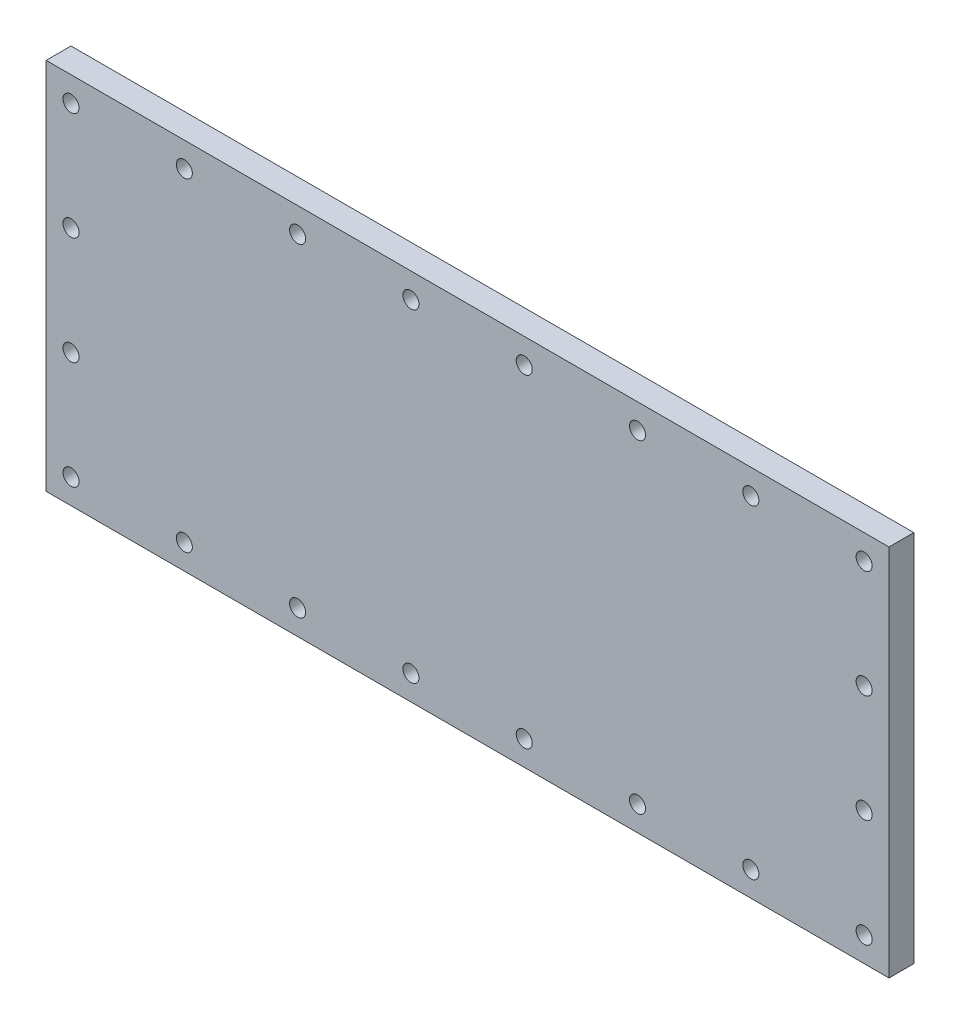
SolidWorks part; units mm, degrees
material "Acrylic (Medium-high impact)"
ref_plane "Front Plane" through (0, 0, 0) normal (0, 0, 1) x (1, 0, 0)
ref_plane "Top Plane" through (0, 0, 0) normal (0, 1, 0) x (1, 0, 0)
ref_plane "Right Plane" through (0, 0, 0) normal (1, 0, 0) x (0, 0, -1)
sketch "Sketch1" plane through (0, 0, 0) normal (0, 0, 1) x (1, 0, 0)
  line L1 (-53.85, -23.85) -> (53.85, -23.85)
  line L2 (-53.85, -23.85) -> (-53.85, 23.85)
  line L3 (-53.85, 23.85) -> (53.85, 23.85)
  line L4 (53.85, -23.85) -> (53.85, 23.85)
  line L5 (-53.85, -23.85) -> (53.85, 23.85) construction
  line L6 (-53.85, 23.85) -> (53.85, -23.85) construction
  line L7 (-50.675, 20.675) -> (50.675, 20.675) construction
  line L8 (-50.675, 20.675) -> (-50.675, -20.675) construction
  line L9 (-50.675, -20.675) -> (50.675, -20.675) construction
  line L10 (50.675, 20.675) -> (50.675, -20.675) construction
  line L11 (-47.5, 17.5) -> (47.5, 17.5)
  line L12 (-47.5, 17.5) -> (-47.5, -17.5)
  line L13 (-47.5, -17.5) -> (47.5, -17.5)
  line L14 (47.5, 17.5) -> (47.5, -17.5)
  circle A0 centre (-50.675, 20.675) radius 1.025
  circle A1 centre (50.675, 20.675) radius 1.025
  circle A2 centre (-50.675, -20.675) radius 1.025
  circle A3 centre (50.675, -20.675) radius 1.025
  circle A4 centre (-7.2393, 20.675) radius 1.025
  circle A5 centre (-7.2393, -20.675) radius 1.025
  circle A8 centre (-36.1964, 20.675) radius 1.025
  circle A9 centre (-21.7179, 20.675) radius 1.025
  circle A10 centre (7.2393, 20.675) radius 1.025
  circle A11 centre (21.7179, 20.675) radius 1.025
  circle A12 centre (-50.675, 6.8917) radius 1.025
  circle A13 centre (-50.675, -6.8917) radius 1.025
  circle A14 centre (50.675, 6.8917) radius 1.025
  circle A15 centre (50.675, -6.8917) radius 1.025
  circle A16 centre (7.2393, -20.675) radius 1.025
  circle A17 centre (21.7179, -20.675) radius 1.025
  circle A18 centre (-21.7179, -20.675) radius 1.025
  circle A19 centre (-36.1964, -20.675) radius 1.025
  circle A20 centre (36.1964, 20.675) radius 1.025
  circle A21 centre (36.1964, -20.675) radius 1.025
  point P0 (0, 0)
  dimension "D7" = 2.05
  dimension "D1" = 107.7
  dimension "D2" = 47.7
  dimension "D3" = 3.175
  dimension "D4" = 3.175
  dimension "D5" = 3.175
  dimension "D6" = 3.175
  dimension "D8" = 41.35
  dimension "D9" = 13.7833
  dimension "D10" = 13.7833
  dimension "D11" = 101.35
  dimension "D12" = 14.4786
  dimension "D13" = 14.4786
  dimension "D14" = 14.4786
  dimension "D15" = 14.4786
  dimension "D16" = 6.35
  dimension "D17" = 6.35
  dimension "D18" = 6.35
  dimension "D19" = 6.35
  dimension "D20" = 14.4786
  dimension "D21" = 14.4786
extrude "Boss-Extrude1" add sketch "Sketch1" along normal blind 3.175 contours L1 L4 L3 L2 A19 A18 A17 A16 A15 A14 A13 A12 A11 A10 A9 A8 A5 A4 A3 A2 A1 A0 | L12 L11 L14 L13
chamfer "Chamfer1" distance 1 angle 45 20 edges at (51.7, -20.675, 0) (22.7429, -20.675, 0) (8.2643, -20.675, 0) (-6.2143, -20.675, 0) (-20.6929, -20.675, 0) (-35.1714, -20.675, 0) (-49.65, -20.675, 0) (-49.65, -6.8917, 0) (-49.65, 6.8917, 0) (-49.65, 20.675, 0) (-35.1714, 20.675, 0) (-20.6929, 20.675, 0) (-6.2143, 20.675, 0) (8.2643, 20.675, 0) (22.7429, 20.675, 0) (51.7, 20.675, 0) (51.7, 6.8917, 0) (51.7, -6.8917, 0) (37.2214, -20.675, 0) (37.2214, 20.675, 0)
